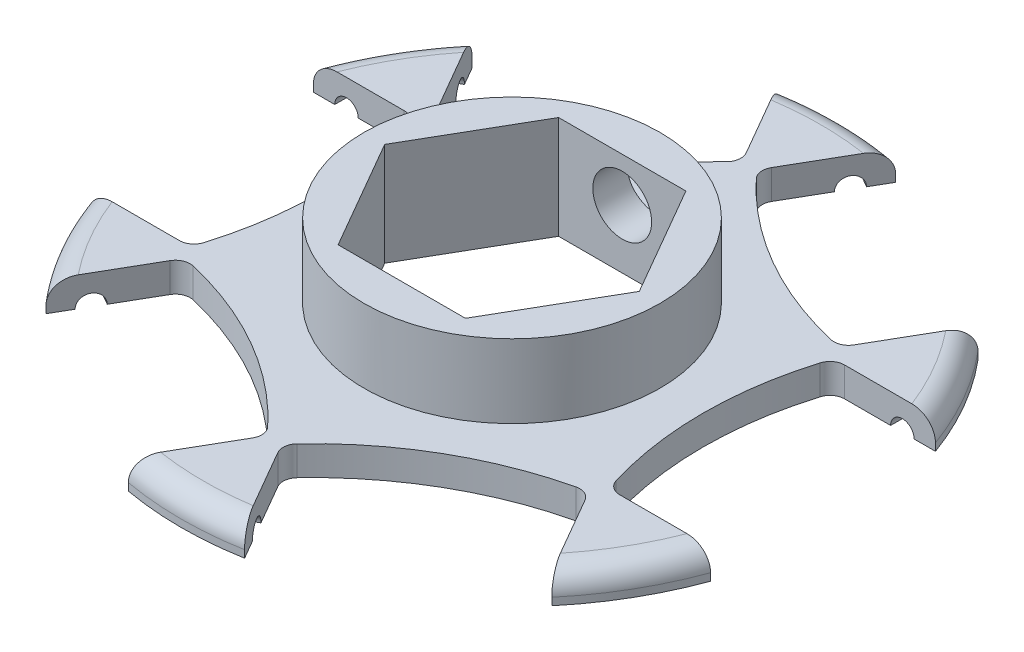
SolidWorks part; units mm, degrees
ref_plane "Ebene vorne" through (0, 0, 0) normal (0, 0, 1) x (1, 0, 0)
ref_plane "Ebene oben" through (0, 0, 0) normal (0, 1, 0) x (1, 0, 0)
ref_plane "Ebene rechts" through (0, 0, 0) normal (1, 0, 0) x (0, 0, -1)
sketch "Skizze1" plane through (0, 0, 0) normal (0, 1, 0) x (1, 0, 0)
  circle A0 centre (0, 0) radius 45
  dimension "D1" = 90
extrude "Aufsatz-Linear austragen1" add sketch "Skizze1" along normal blind 4
sketch "Skizze2" plane through (0, 4, 0) normal (0, 1, 0) x (1, 0, 0)
  line L0 (-28.5037, 15.3) -> (-71.0776, 15.3)
  line L1 (-28.5037, -15.3) -> (-71.0776, -15.3)
  line L2 (-71.0776, 15.3) -> (-71.0776, -15.3)
  circle A0 centre (-74, 0) radius 48
  circle M2 centre (0, 0) radius 45
  dimension "D1" = 74
  dimension "D2" = 96
  dimension "D3" = 30.6
  dimension "D4" = 15.3
extrude "Schnitt-Linear austragen2" cut sketch "Skizze2" against normal blind 10 contours L1 A0 L0 M2
pattern_circular "Kreismuster1" count 6 over 360 about axis through (0, 0, 0) along (0, 1, 0) of "Schnitt-Linear austragen2"
sketch "Skizze4" plane through (0, 4, 0) normal (0, 1, 0) x (1, 0, 0)
  circle A0 centre (0, 0) radius 20.15
extrude "Aufsatz-Linear austragen2" add sketch "Skizze4" along normal blind 10 contours A0
sketch "Skizze3" plane through (0, 0, 0) normal (0, -1, 0) x (1, 0, 0)
  line L1 (17.3205, 0) -> (8.6603, 15)
  line L2 (8.6603, 15) -> (-8.6603, 15)
  line L3 (-8.6603, 15) -> (-17.3205, 0)
  line L4 (-17.3205, 0) -> (-8.6603, -15)
  line L5 (-8.6603, -15) -> (8.6603, -15)
  line L6 (8.6603, -15) -> (17.3205, 0)
  circle A0 centre (0, 0) radius 15 construction
  dimension "D1" = 30
extrude "Schnitt-Linear austragen3" cut sketch "Skizze3" against normal blind 16
fillet "Verrundung1" radius 2 12 edges at (-28.5037, 2, 15.3) (-1.0017, 2, 32.335) (1.0017, 2, 32.335) (27.5021, 2, 17.035) (28.5037, 2, 15.3) (28.5037, 2, -15.3) (27.5021, 2, -17.035) (1.0017, 2, -32.335) (-1.0017, 2, -32.335) (-27.5021, 2, -17.035) (-28.5037, 2, -15.3) (-27.5021, 2, 17.035)
sketch "Skizze5" plane through (13.2502, 0, 7.65) normal (-0.866, 0, -0.5) x (-0.5, 0, 0.866)
  line L0 (-29.9647, 0) -> (-42.3191, 0) construction
  line L1 (-42.3191, 0) -> (-42.3191, 4) construction
  circle A0 centre (-37.8191, 0) radius 1.6
  dimension "D1" = 4.5
extrude "Schnitt-Linear austragen5" cut sketch "Skizze5" against normal blind 3.8 contours A0
fillet "Verrundung3" radius 0.5 1 edges at (35.4507, 1.6, -23.2023)
pattern_circular "Kreismuster2" count 6 over 360 about axis through (0, 0, 0) along (0, 1, 0) of "Schnitt-Linear austragen5", "Verrundung3"
sketch "Skizze6" plane through (0, 0, -15.3) normal (0, 0, 1) x (1, 0, 0)
  line L0 (29.9647, 0) -> (42.3191, 0) construction
  line L1 (42.3191, 0) -> (42.3191, 4) construction
  circle A0 centre (37.8191, 0) radius 1.6
  dimension "D1" = 4.5
extrude "Schnitt-Linear austragen6" cut sketch "Skizze6" against normal blind 3.8
fillet "Verrundung4" radius 0.5 1 edges at (37.8191, 1.6, -19.1)
pattern_circular "Kreismuster3" count 6 over 360 about axis through (0, 0, 0) along (0, 1, 0) of "Schnitt-Linear austragen6", "Verrundung4"
sketch "Zentrierung" plane through (0, 0, 0) normal (0, -1, 0) x (1, 0, 0)
  circle A0 centre (0, 0) radius 20
fillet "Verrundung2" radius 3 6 edges at (0, 4, -45) (-38.9711, 4, -22.5) (-38.9711, 4, 22.5) (0, 4, 45) (38.9711, 4, 22.5) (38.9711, 4, -22.5)
sketch "Skizze7" plane through (0, 0, -15) normal (0, 0, 1) x (1, 0, 0)
  circle A0 centre (0, 8) radius 4
extrude "Schnitt-Linear austragen7" cut sketch "Skizze7" against normal blind 10
